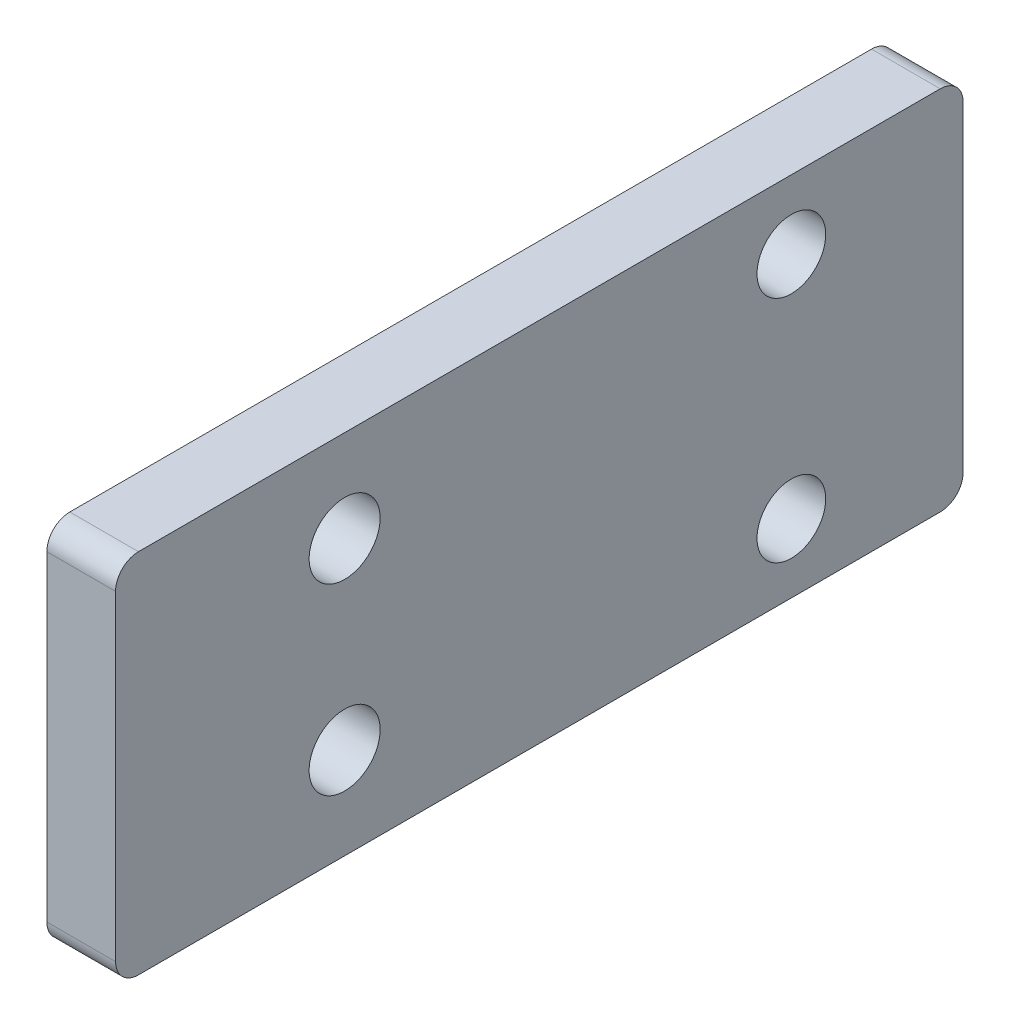
SolidWorks part; units mm, degrees
material "Thornel Mat VMA"
ref_plane "前视基准面" through (0, 0, 0) normal (0, 0, 1) x (1, 0, 0)
ref_plane "上视基准面" through (0, 0, 0) normal (0, 1, 0) x (1, 0, 0)
ref_plane "右视基准面" through (0, 0, 0) normal (1, 0, 0) x (0, 0, -1)
sketch "草图1" plane through (0, 0, 0) normal (1, 0, 0) x (0, 0, -1)
  line L0 (3.5, 8) -> (3.5, -8) construction
  line L1 (18.5, -8) -> (-18.5, -8)
  line L2 (18.5, -8) -> (18.5, 8)
  line L3 (18.5, 8) -> (-18.5, 8)
  line L4 (-18.5, -8) -> (-18.5, 8)
  line L5 (18.5, -8) -> (-18.5, 8) construction
  line L6 (18.5, 8) -> (-18.5, -8) construction
  line L7 (11, 8) -> (11, -8) construction
  line L8 (0, 0) -> (18.5, 0) construction
  line L14 (-8.5, 8) -> (-8.5, -0.4492) construction
  circle A0 centre (11, 5) radius 1.5
  circle A1 centre (11, -5) radius 1.5
  circle A14 centre (11, 5) radius 2.75 construction
  circle A15 centre (-8.5, 4) radius 1.55
  circle A17 centre (-12, -4) radius 1.55 construction
  circle A18 centre (-5, -4) radius 1.55 construction
  circle A19 centre (-8.5, -4) radius 1.55
  point P0 (0, 0)
  dimension "D6" = 3
  dimension "D12" = 8
  dimension "D16" = 5.5
  dimension "D9" = 3.1
  dimension "D1" = 16
  dimension "D2" = 22
  dimension "D3" = 15
  dimension "D4" = 7.5
  dimension "D5" = 10
  dimension "D7" = 12
  dimension "D8" = 7
  dimension "D10" = 8
  dimension "D11" = 4
extrude "凸台-拉伸1" add sketch "草图1" along normal blind 3
fillet "圆角1" radius 1 4 edges at (1.5, 8, -18.5) (1.5, -8, -18.5) (1.5, -8, 18.5) (1.5, 8, 18.5)
